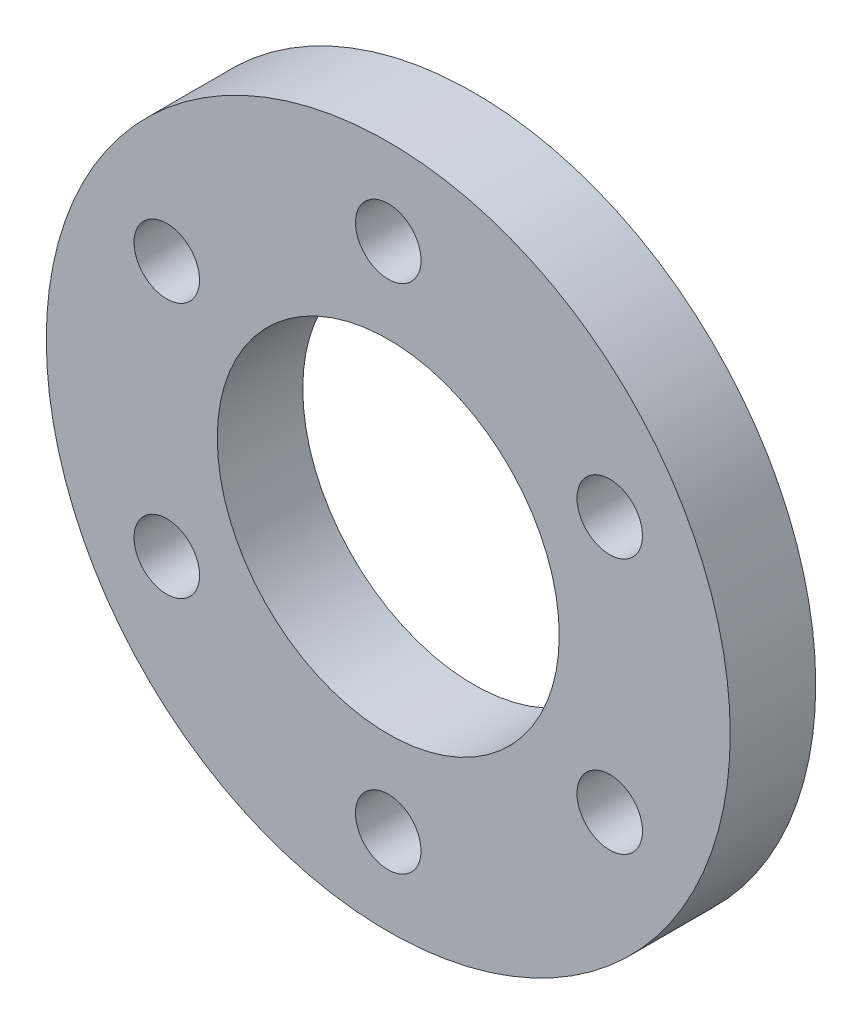
SolidWorks part; units mm, degrees
ref_plane "Front Plane" through (0, 0, 0) normal (0, 0, 1) x (1, 0, 0)
ref_plane "Top Plane" through (0, 0, 0) normal (0, 1, 0) x (1, 0, 0)
ref_plane "Right Plane" through (0, 0, 0) normal (1, 0, 0) x (0, 0, -1)
sketch "Sketch1" plane through (0, 0, 0) normal (0, 0, 1) x (1, 0, 0)
  circle A0 centre (0, 0) radius 40
  circle A1 centre (0, 0) radius 20
  dimension "D1" = 80
  dimension "D2" = 40
extrude "Boss-Extrude1" add sketch "Sketch1" along normal blind 10
sketch "Sketch2" plane through (0, 0, 10) normal (0, 0, 1) x (1, 0, 0)
  circle A0 centre (0, 0) radius 29.9112 construction
  circle A1 centre (0, 29.9112) radius 3.8315
extrude "Cut-Extrude1" cut sketch "Sketch2" against normal blind 10
pattern_circular "CirPattern1" count 6 over 360 about axis through (0, 0, 0) along (0, 0, 1) of "Cut-Extrude1"
